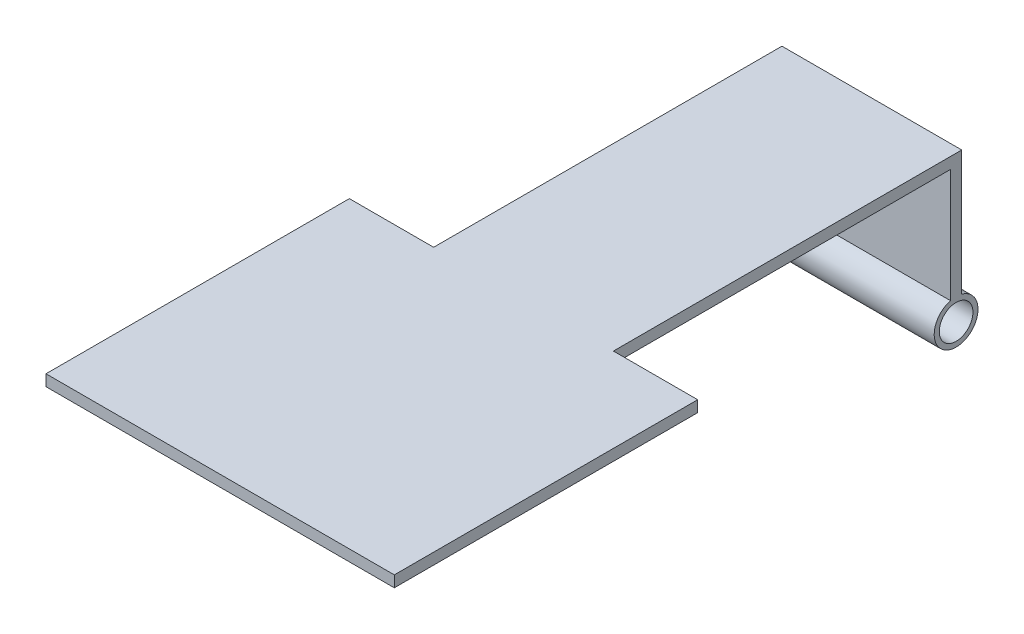
SolidWorks part; units mm, degrees
ref_plane "Front Plane" through (0, 0, 0) normal (0, 0, 1) x (1, 0, 0)
ref_plane "Top Plane" through (0, 0, 0) normal (0, 1, 0) x (1, 0, 0)
ref_plane "Right Plane" through (0, 0, 0) normal (1, 0, 0) x (0, 0, -1)
sketch "Sketch1" plane through (0, 0, 0) normal (1, 0, 0) x (0, 0, -1)
  line L0 (0, 0) -> (0, 1.9499)
  line L1 (0, 12.9999) -> (0.4995, 12.9999)
  line L2 (0.4995, 12.9999) -> (-0.5005, 12.9999)
  line L3 (-0.5005, 12.9999) -> (-0.5005, 1.8847)
  line L4 (0.4995, 12.9999) -> (0.4995, 1.8849)
  arc A0 (-0.5005, 1.8847) -> (0.4995, 1.8849) centre (0, 0) ccw
  circle A1 centre (0, 0) radius 1.5
extrude "Boss-Extrude1" add sketch "Sketch1" along normal blind 16
sketch "Sketch2" plane through (0, 12.9999, 0) normal (0, 1, 0) x (1, 0, 0)
  line L0 (0, 0) -> (0, -30.5005)
  line L1 (0, 0) -> (16, -0.0005)
  line L2 (16, -0.5005) -> (16, 0.4995) construction
  line L5 (16, -0.0005) -> (16, -30.5005)
  line L6 (16, -30.5005) -> (23.5, -30.5005)
  line L7 (16, -30.5005) -> (23.5, -30.5005)
  line L8 (0, -30.5005) -> (-7.5, -30.5005)
  line L9 (-7.5, -30.5005) -> (0, -30.5005)
  line L10 (-7.5, -30.5005) -> (-7.5, -57.5)
  line L11 (-7.5, -57.5) -> (23.5, -57.5)
  line L12 (23.5, -30.5005) -> (23.5, -57.5)
  line M13 (0, -0.5005) -> (16, -0.5005)
extrude "Boss-Extrude2" add sketch "Sketch2" against normal blind 1 contours L12 L6 L5 L0 L8 L10 L11 M13
